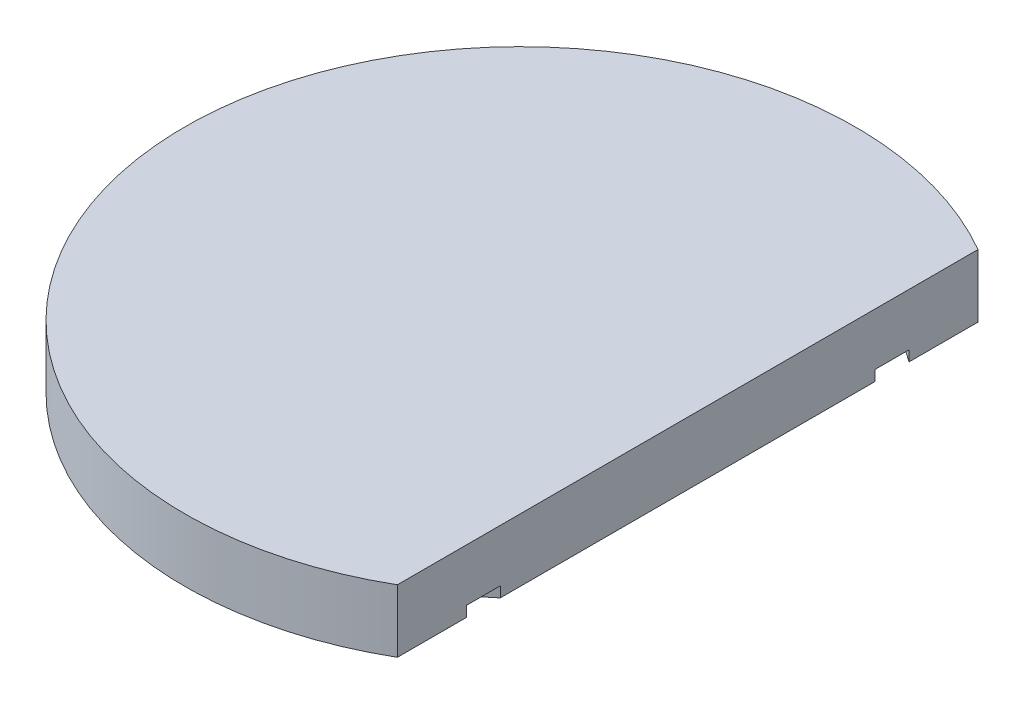
SolidWorks part; units mm, degrees
ref_plane "Front Plane" through (0, 0, 0) normal (0, 0, 1) x (1, 0, 0)
ref_plane "Top Plane" through (0, 0, 0) normal (0, 1, 0) x (1, 0, 0)
ref_plane "Right Plane" through (0, 0, 0) normal (1, 0, 0) x (0, 0, -1)
sketch "Sketch1" plane through (0, 0, 0) normal (0, 1, 0) x (1, 0, 0)
  line L0 (-152.8916, 0) -> (152.8916, 0) construction
  line L1 (0, -114.2418) -> (0, 114.2418) construction
  line L2 (50.8, -87.9882) -> (50.8, 87.9882)
  line L3 (-34.925, -47.625) -> (34.925, -47.625) construction
  line L4 (-47.625, -34.925) -> (-47.625, 34.925) construction
  line L5 (-34.925, 47.625) -> (34.925, 47.625) construction
  line L6 (47.625, -34.925) -> (47.625, 34.925) construction
  line L7 (-47.625, -47.625) -> (47.625, 47.625) construction
  line L8 (-47.625, 47.625) -> (47.625, -47.625) construction
  circle A0 centre (0, 0) radius 84.1375 construction
  circle A1 centre (0, 0) radius 76.2 construction
  circle A2 centre (0, 0) radius 101.6 construction
  arc A3 (34.925, 47.625) -> (47.625, 34.925) centre (34.925, 34.925) cw construction
  arc A4 (34.925, -47.625) -> (47.625, -34.925) centre (34.925, -34.925) ccw construction
  arc A5 (-34.925, -47.625) -> (-47.625, -34.925) centre (-34.925, -34.925) cw construction
  arc A6 (-47.625, 34.925) -> (-34.925, 47.625) centre (-34.925, 34.925) cw construction
  arc A7 (50.8, 87.9882) -> (50.8, -87.9882) centre (0, 0) ccw
  point P4 (0, 0)
  point P8 (0, 0)
  point P31 (50.8, 0)
  dimension "D1" = 168.275
  dimension "D2" = 152.4
  dimension "D3" = 203.2
  dimension "D6" = 12.7
  dimension "D4" = 95.25
  dimension "D5" = 95.25
  dimension "D7" = 6.35
extrude "Boss-Extrude1" add sketch "Sketch1" along normal blind 19.05
sketch "Sketch2" plane through (0, 0, 0) normal (0, -1, 0) x (1, 0, 0)
  line L0 (-149.5491, 0) -> (149.5491, 0) construction
  line L1 (0, -137.0638) -> (0, 137.0638) construction
  circle A0 centre (0, 0) radius 76.2
  circle A1 centre (0, 0) radius 84.1375
  point P4 (0, 0)
  point P8 (0, 0)
  dimension "D1" = 152.4
  dimension "D2" = 168.275
extrude "Cut-Extrude1" cut sketch "Sketch2" against normal blind 3.175
